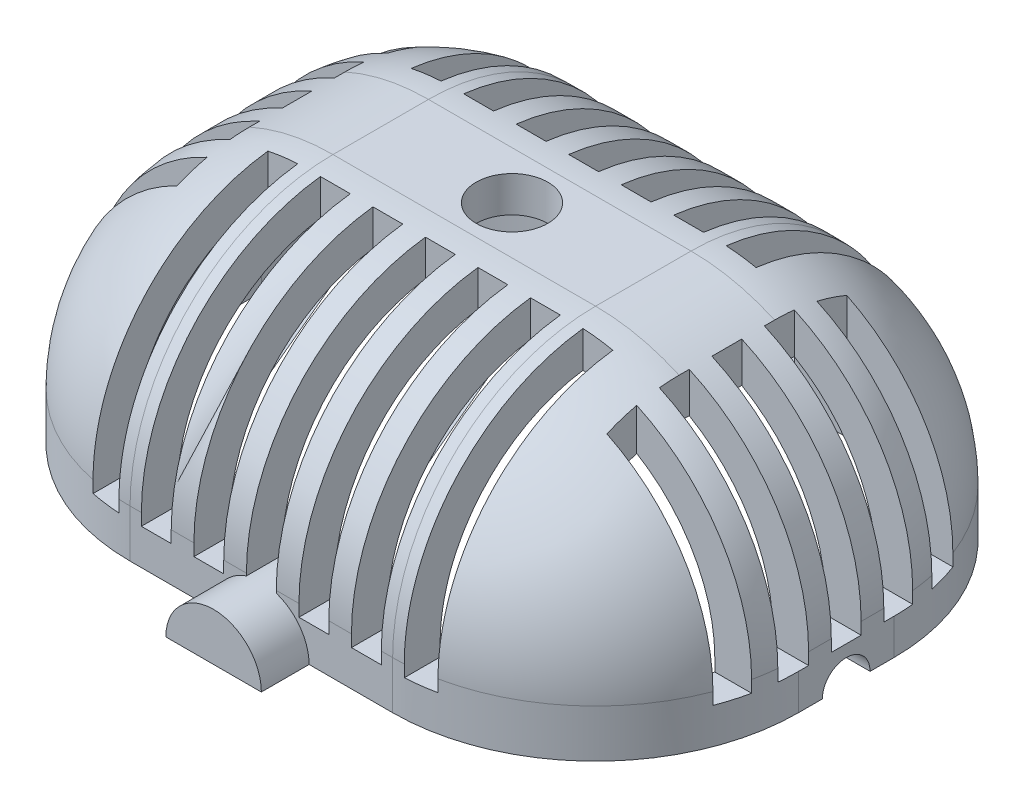
SolidWorks part; units mm, degrees
ref_plane "Спереди" through (0, 0, 0) normal (0, 0, 1) x (1, 0, 0)
ref_plane "Сверху" through (0, 0, 0) normal (0, 1, 0) x (1, 0, 0)
ref_plane "Справа" through (0, 0, 0) normal (1, 0, 0) x (0, 0, -1)
sketch "Эскиз1" plane through (0, 0, 0) normal (0, 1, 0) x (1, 0, 0)
  line L1 (12.5, -9) -> (-12.5, -9)
  line L2 (12.5, -9) -> (12.5, 9)
  line L3 (12.5, 9) -> (-12.5, 9)
  line L4 (-12.5, -9) -> (-12.5, 9)
  line L5 (12.5, -9) -> (-12.5, 9) construction
  line L6 (12.5, 9) -> (-12.5, -9) construction
  point P0 (0, 0)
  dimension "D1" = 25
  dimension "D2" = 18
extrude "Бобышка-Вытянуть1" add sketch "Эскиз1" along normal blind 9
fillet "Скругление1" radius 7 8 edges at (0, 9, -9) (0, 9, 9) (-12.5, 4.5, -9) (-12.5, 4.5, 9) (12.5, 4.5, -9) (12.5, 4.5, 9) (12.5, 9, 0) (-12.5, 9, 0)
shell "Оболочка2" thickness 1.5
sketch "Эскиз2" plane through (0, 10.5, 0) normal (0, 1, 0) x (1, 0, 0)
  line L0 (-5.5, 10.5) -> (5.5, 10.5) construction
  line L1 (-0.625, 18) -> (0.625, 18)
  line L2 (-0.625, 18) -> (-0.625, 3)
  line L3 (-0.625, 3) -> (0.625, 3)
  line L4 (0.625, 18) -> (0.625, 3)
  line L5 (-0.625, 18) -> (0.625, 3) construction
  line L6 (-0.625, 3) -> (0.625, 18) construction
  line L7 (1.575, 18) -> (2.825, 18)
  line L8 (1.575, 18) -> (1.575, 3)
  line L9 (2.825, 18) -> (2.825, 3)
  line L10 (1.575, 3) -> (2.825, 3)
  line L11 (3.775, 18) -> (5.025, 18)
  line L12 (3.775, 18) -> (3.775, 3)
  line L13 (5.025, 18) -> (5.025, 3)
  line L14 (3.775, 3) -> (5.025, 3)
  line L15 (5.975, 18) -> (7.225, 18)
  line L16 (5.975, 18) -> (5.975, 3)
  line L17 (7.225, 18) -> (7.225, 3)
  line L18 (5.975, 3) -> (7.225, 3)
  line L19 (-0.625, 18) -> (0.625, 18)
  line L20 (-0.625, 18) -> (-0.625, 3)
  line L21 (0.625, 18) -> (0.625, 3)
  line L22 (-0.625, 3) -> (0.625, 3)
  line L23 (1.575, 18) -> (2.825, 18)
  line L24 (1.575, 18) -> (1.575, 3)
  line L25 (2.825, 18) -> (2.825, 3)
  line L26 (1.575, 3) -> (2.825, 3)
  line L27 (3.775, 18) -> (5.025, 18)
  line L28 (3.775, 18) -> (3.775, 3)
  line L29 (5.025, 18) -> (5.025, 3)
  line L30 (3.775, 3) -> (5.025, 3)
  line L31 (-2.825, 18) -> (-1.575, 18)
  line L32 (-2.825, 18) -> (-2.825, 3)
  line L33 (-1.575, 18) -> (-1.575, 3)
  line L34 (-2.825, 3) -> (-1.575, 3)
  line L35 (-0.625, 18) -> (0.625, 18)
  line L36 (-0.625, 18) -> (-0.625, 3)
  line L37 (0.625, 18) -> (0.625, 3)
  line L38 (-0.625, 3) -> (0.625, 3)
  line L39 (1.575, 18) -> (2.825, 18)
  line L40 (1.575, 18) -> (1.575, 3)
  line L41 (2.825, 18) -> (2.825, 3)
  line L42 (1.575, 3) -> (2.825, 3)
  line L43 (-5.025, 18) -> (-3.775, 18)
  line L44 (-5.025, 18) -> (-5.025, 3)
  line L45 (-3.775, 18) -> (-3.775, 3)
  line L46 (-5.025, 3) -> (-3.775, 3)
  line L47 (-2.825, 18) -> (-1.575, 18)
  line L48 (-2.825, 18) -> (-2.825, 3)
  line L49 (-1.575, 18) -> (-1.575, 3)
  line L50 (-2.825, 3) -> (-1.575, 3)
  line L51 (-0.625, 18) -> (0.625, 18)
  line L52 (-0.625, 18) -> (-0.625, 3)
  line L53 (0.625, 18) -> (0.625, 3)
  line L54 (-0.625, 3) -> (0.625, 3)
  line L55 (-2.825, 18) -> (-1.575, 18)
  line L56 (-2.825, 18) -> (-2.825, 3)
  line L57 (-1.575, 18) -> (-1.575, 3)
  line L58 (-2.825, 3) -> (-1.575, 3)
  line L59 (-5.025, 18) -> (-3.775, 18)
  line L60 (-5.025, 18) -> (-5.025, 3)
  line L61 (-3.775, 18) -> (-3.775, 3)
  line L62 (-5.025, 3) -> (-3.775, 3)
  line L63 (-7.225, 18) -> (-5.975, 18)
  line L64 (-7.225, 18) -> (-7.225, 3)
  line L65 (-5.975, 18) -> (-5.975, 3)
  line L66 (-7.225, 3) -> (-5.975, 3)
  line L67 (-0.625, 18) -> (1.575, 18) construction
  circle A0 centre (0, 0) radius 1.5
  point P0 (0, 10.5)
  dimension "D6" = 3
  dimension "D1" = 1.25
  dimension "D2" = 3
  dimension "D5" = 2.2
  dimension "D3" = 4
  dimension "D4" = 4
extrude "Вырез-Вытянуть1" cut sketch "Эскиз2" against normal blind 9 contours L8 L10 L9 L7 | L12 L14 L13 L11 | L16 L18 L17 L15 | L4 L1 L2 L3 | L32 L34 L33 L31 | L44 L46 L45 L43 | L64 L66 L65 L63 | A0
sketch "Эскиз3" plane through (0, 10.5, 0) normal (0, 1, 0) x (1, 0, 0)
  line L0 (-15.332, 0) -> (0, 0) construction
  line L1 (-21.664, -0.625) -> (-9, -0.625)
  line L2 (-21.664, -0.625) -> (-21.664, 0.625)
  line L3 (-21.664, 0.625) -> (-9, 0.625)
  line L4 (-9, -0.625) -> (-9, 0.625)
  line L5 (-21.664, -0.625) -> (-9, 0.625) construction
  line L6 (-21.664, 0.625) -> (-9, -0.625) construction
  line L7 (-21.664, -2.825) -> (-9, -2.825)
  line L8 (-21.664, -2.825) -> (-21.664, -1.575)
  line L9 (-21.664, -1.575) -> (-9, -1.575)
  line L10 (-9, -2.825) -> (-9, -1.575)
  line L11 (-21.664, -5.025) -> (-9, -5.025)
  line L12 (-21.664, -5.025) -> (-21.664, -3.775)
  line L13 (-21.664, -3.775) -> (-9, -3.775)
  line L14 (-9, -5.025) -> (-9, -3.775)
  line L19 (-21.664, -0.625) -> (-9, -0.625)
  line L20 (-21.664, -0.625) -> (-21.664, 0.625)
  line L21 (-21.664, 0.625) -> (-9, 0.625)
  line L22 (-9, -0.625) -> (-9, 0.625)
  line L23 (-21.664, -2.825) -> (-9, -2.825)
  line L24 (-21.664, -2.825) -> (-21.664, -1.575)
  line L25 (-21.664, -1.575) -> (-9, -1.575)
  line L26 (-9, -2.825) -> (-9, -1.575)
  line L31 (-21.664, 1.575) -> (-9, 1.575)
  line L32 (-21.664, 1.575) -> (-21.664, 2.825)
  line L33 (-21.664, 2.825) -> (-9, 2.825)
  line L34 (-9, 1.575) -> (-9, 2.825)
  line L35 (-21.664, -0.625) -> (-9, -0.625)
  line L36 (-21.664, -0.625) -> (-21.664, 0.625)
  line L37 (-21.664, 0.625) -> (-9, 0.625)
  line L38 (-9, -0.625) -> (-9, 0.625)
  line L55 (-21.664, 1.575) -> (-9, 1.575)
  line L56 (-21.664, 1.575) -> (-21.664, 2.825)
  line L57 (-21.664, 2.825) -> (-9, 2.825)
  line L58 (-9, 1.575) -> (-9, 2.825)
  line L59 (-21.664, 3.775) -> (-9, 3.775)
  line L60 (-21.664, 3.775) -> (-21.664, 5.025)
  line L61 (-21.664, 5.025) -> (-9, 5.025)
  line L62 (-9, 3.775) -> (-9, 5.025)
  line L67 (-21.664, -0.625) -> (-21.664, -2.825) construction
  point P0 (-15.332, 0)
  dimension "D1" = 9
  dimension "D2" = 1.25
  dimension "D5" = 2.2
  dimension "D3" = 3
  dimension "D4" = 3
extrude "Вырез-Вытянуть2" cut sketch "Эскиз3" against normal blind 9 contours L7 L10 L9 L8 | L1 L4 L3 L2 | L31 L34 L33 L32 | L59 L62 L61 L60 | L11 L14 L13 L12
mirror "Зеркальное отражение1" about plane through (0, 0, 0) normal (0, 0, 1) of "Вырез-Вытянуть1"
mirror "Зеркальное отражение2" about plane through (0, 0, 0) normal (1, 0, 0) of "Вырез-Вытянуть2"
sketch "Эскиз5" plane through (0, 0, -9) normal (0, 0, 1) x (1, 0, 0)
  line L0 (5.5, 0) -> (-5.5, 0) construction
  line L1 (-2, 0) -> (2, 0)
  arc A0 (2, 0) -> (-2, 0) centre (0, 0) ccw
  dimension "D1" = 4
extrude "Бобышка-Вытянуть2" add sketch "Эскиз5" against normal blind 3.5
mirror "Зеркальное отражение3" about plane through (0, 0, 0) normal (0, 0, 1) of "Бобышка-Вытянуть2"
sketch "Эскиз6" plane through (14, 0, 0) normal (1, 0, 0) x (0, 0, -1)
  line L0 (-2, 0) -> (2, 0) construction
  line L1 (-1, 0) -> (1, 0)
  arc A0 (1, 0) -> (-1, 0) centre (0, 0) ccw
  dimension "D1" = 2
extrude "Вырез-Вытянуть3" cut sketch "Эскиз6" against normal up to next
